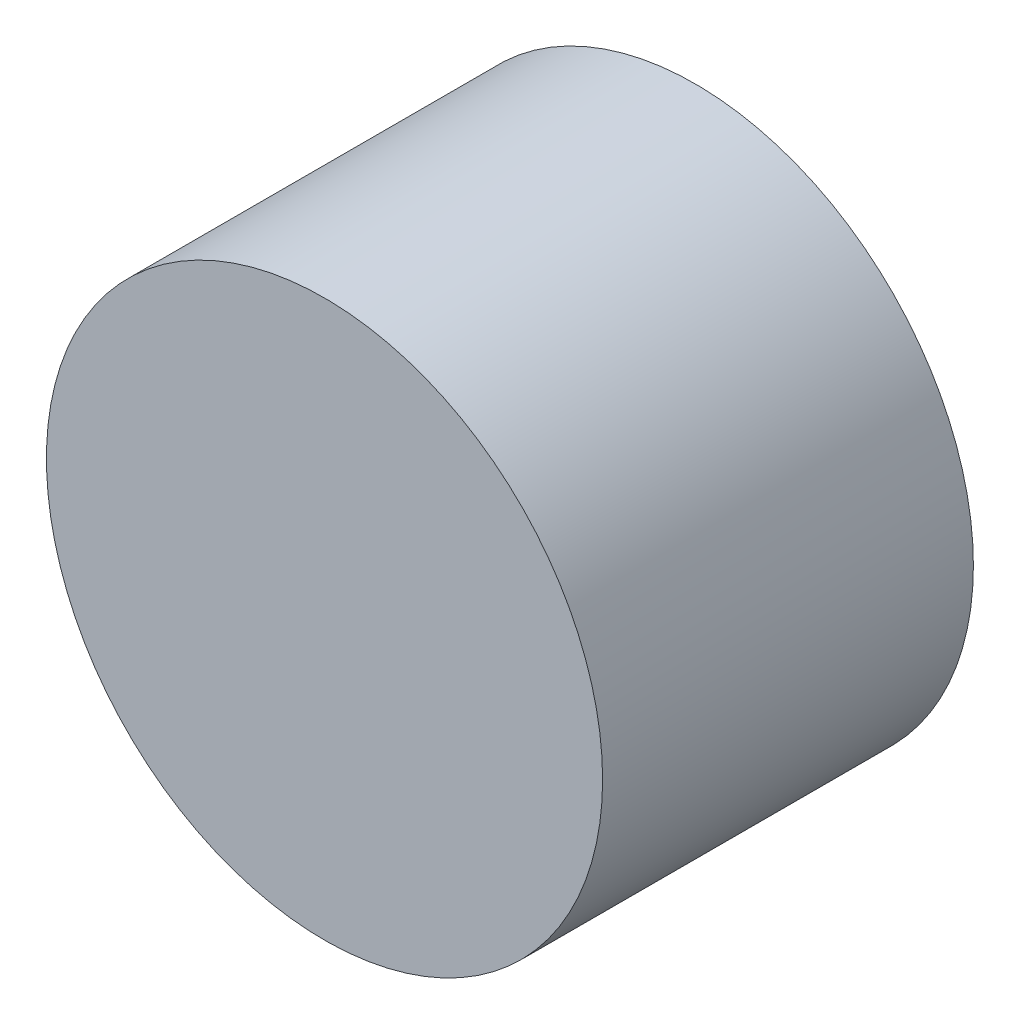
SolidWorks part; units mm, degrees
ref_plane "Ebene vorne" through (0, 0, 0) normal (0, 0, 1) x (1, 0, 0)
ref_plane "Ebene oben" through (0, 0, 0) normal (0, 1, 0) x (1, 0, 0)
ref_plane "Ebene rechts" through (0, 0, 0) normal (1, 0, 0) x (0, 0, -1)
sketch "Sketch1" plane through (0, 0, 0) normal (0, 0, 1) x (1, 0, 0)
  circle A0 centre (0, 0) radius 3
  dimension "D1" = 6
extrude "Boss-Extrude1" add sketch "Sketch1" along normal blind 4
